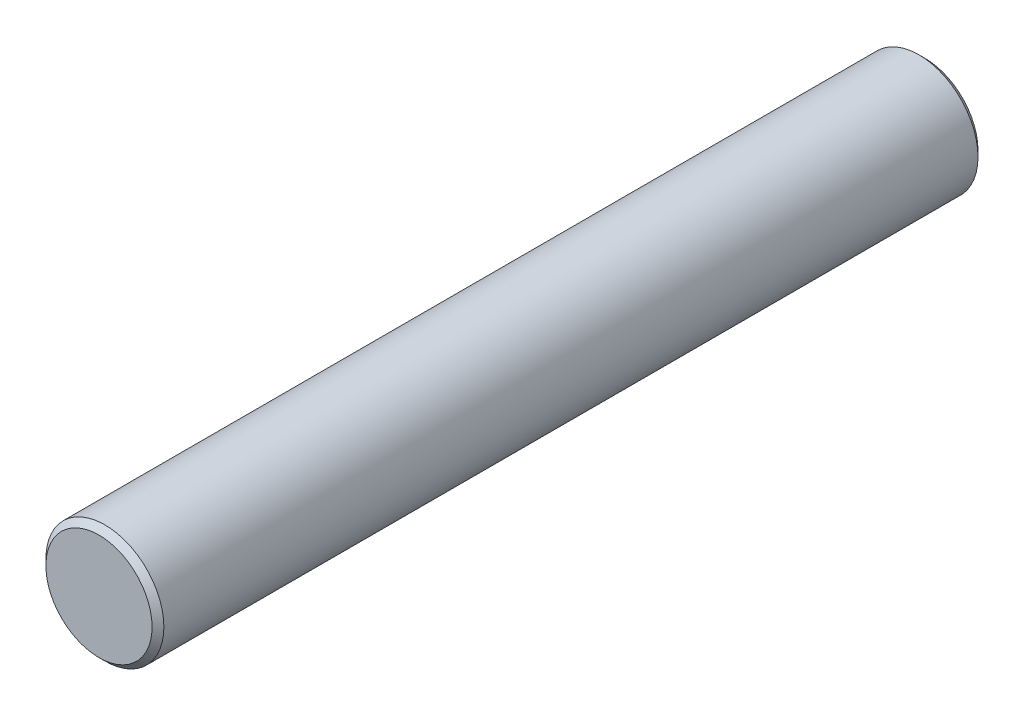
SolidWorks part; units mm, degrees
material "Chrome Stainless Steel"
ref_plane "Front Plane" through (0, 0, 0) normal (0, 0, 1) x (1, 0, 0)
ref_plane "Top Plane" through (0, 0, 0) normal (0, 1, 0) x (1, 0, 0)
ref_plane "Right Plane" through (0, 0, 0) normal (1, 0, 0) x (0, 0, -1)
sketch "Sketch1" plane through (0, 0, 0) normal (0, 0, 1) x (1, 0, 0)
  circle A0 centre (0, 0) radius 2.5
  dimension "D1" = 5
extrude "Boss-Extrude1" add sketch "Sketch1" along normal blind 35 contours A0
chamfer "Chamfer1" distance 0.25 angle 45 2 edges at (2.5, 0, 0) (2.5, 0, 35)
